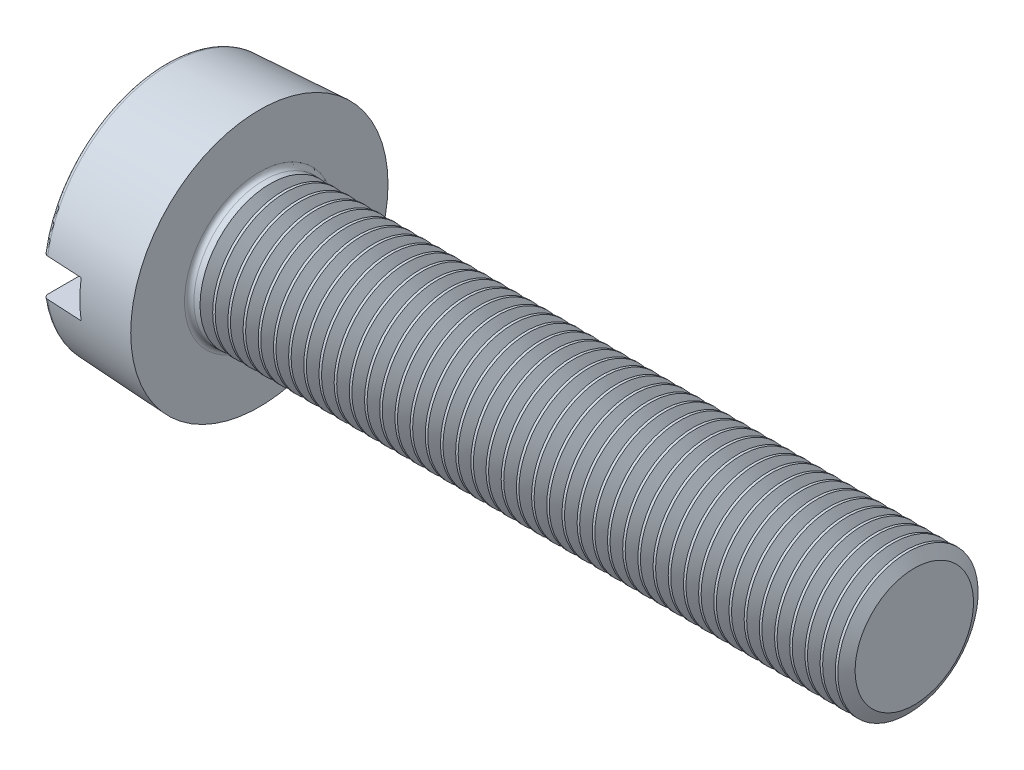
SolidWorks part; units mm, degrees
ref_plane "Front" through (0, 0, 0) normal (0, 0, 1) x (1, 0, 0)
ref_plane "Top" through (0, 0, 0) normal (0, 1, 0) x (1, 0, 0)
ref_plane "Right" through (0, 0, 0) normal (1, 0, 0) x (0, 0, -1)
ref_plane "Plane1" through (2, 0, 0) normal (1, 0, 0) x (0, 0, -1)
sketch "Sketch2" plane through (2, 0, 0) normal (1, 0, 0) x (0, 0, -1)
  circle A0 centre (0, 0) radius 2.75
  dimension "dk" = 5.5
extrude "BaseHead" add sketch "Sketch2" against normal blind 2 draft 3
sketch "Sketch3" plane through (2, -1.1101, -1.3544) normal (1, 0, 0) x (0, 0, -1)
  line L0 (-1.3544, 1.1101) -> (-0.3544, 1.1101) construction
  circle A0 centre (-1.3544, 1.1101) radius 1.5
  circle A1 centre (-1.3544, 1.1101) radius 2.75 construction
  dimension "d" = 3
  dimension "a" = 1
extrude "BaseBody" add sketch "Sketch3" along normal blind 14
cosmetic thread "ThreadCosmetic1" [suppressed] parameters "D1"=14, "D2"=2.459
sketch "Sketch4" plane through (-1.9, -1.9, 0) normal (0, 0, 1) x (0, 1, 0)
  line L1 (1.5, -1.9) -> (2.3, -1.9)
  line L2 (1.5, -1.9) -> (1.5, -2.75)
  line L3 (1.5, -2.75) -> (2.3, -2.75)
  line L4 (2.3, -1.9) -> (2.3, -2.75)
  line L5 (4.5452, -1.9) -> (-0.7452, -1.9) construction
  dimension "n" = 0.8
  dimension "t" = 0.85
  dimension "m" = 0.4
extrude "Slot" cut sketch "Sketch4" against normal through all and the other way through all
fillet "HeadFillet" radius 0.1 3 edges at (2, 0, -1.5) (0, -2.6452, 0) (0, 2.6452, 0)
sketch "Sketch1" plane through (0, 0, 0) normal (0, 0, 1) x (1, 0, 0)
  line L0 (5.5483, 0) -> (-2.9147, 0) construction
  line L1 (2, 6.2295) -> (-9, 6.2295)
  line L2 (2, 6.2295) -> (2, 1.2295)
  line L3 (2, 1.2295) -> (-10.25, 1.2295)
  line L8 (-9, 1.5) -> (-10.25, 1.2295)
  line L9 (-9, 6.2295) -> (-9, 1.5)
  line L10 (2, -2.75) -> (2, 2.75) construction
  line L11 (16, -1.5) -> (16, 1.5) construction
  line L12 (16, 1.5) -> (2.1, 1.5) construction
  dimension "b1" = 2.459
  dimension "b" = 25
  dimension "x" = 1.25
  dimension "dd" = 5
sketch "Sketch5" plane through (0, 0, 0) normal (0, 0, 1) x (1, 0, 0)
  line L0 (16.1352, 1.5) -> (16.1352, 1.7705)
  line L1 (16.1352, 1.7705) -> (15.8647, 1.7705)
  line L2 (15.8647, 1.7705) -> (15.8647, 1.5)
  line L3 (15.8647, 1.5) -> (16, 1.2657)
  line L4 (16, 1.2657) -> (16.1352, 1.5)
  line L5 (16, -1.5) -> (16, 1.5) construction
  line L6 (0, 0) -> (15.9087, 0) construction
  dimension "D1" = 3
  dimension "D2" = 0.2705
revolve "Cut-Revolve10" cut sketch "Sketch5" angle 360 about L6
pattern_linear "LPattern10" count 43 spacing 0.3246 along (-1, 0, 0) of "Cut-Revolve10"
equation "\"m@Sketch4\" = \"n@Sketch4\" / 2"
equation "\"D1@Plane1\"=\"k@BaseHead\""
equation "\"D1@Sketch5\" = \"d@Sketch3\""
equation "\"D2@Sketch5\" =  ( \"d@Sketch3\" - \"D2@ThreadCosmetic1\" )  / 2"
equation "\"D3@LPattern10\" = \"D2@Sketch5\" * 1.2"
equation "\"D1@LPattern10\" = \"D1@ThreadCosmetic1\" / \"D3@LPattern10\""
